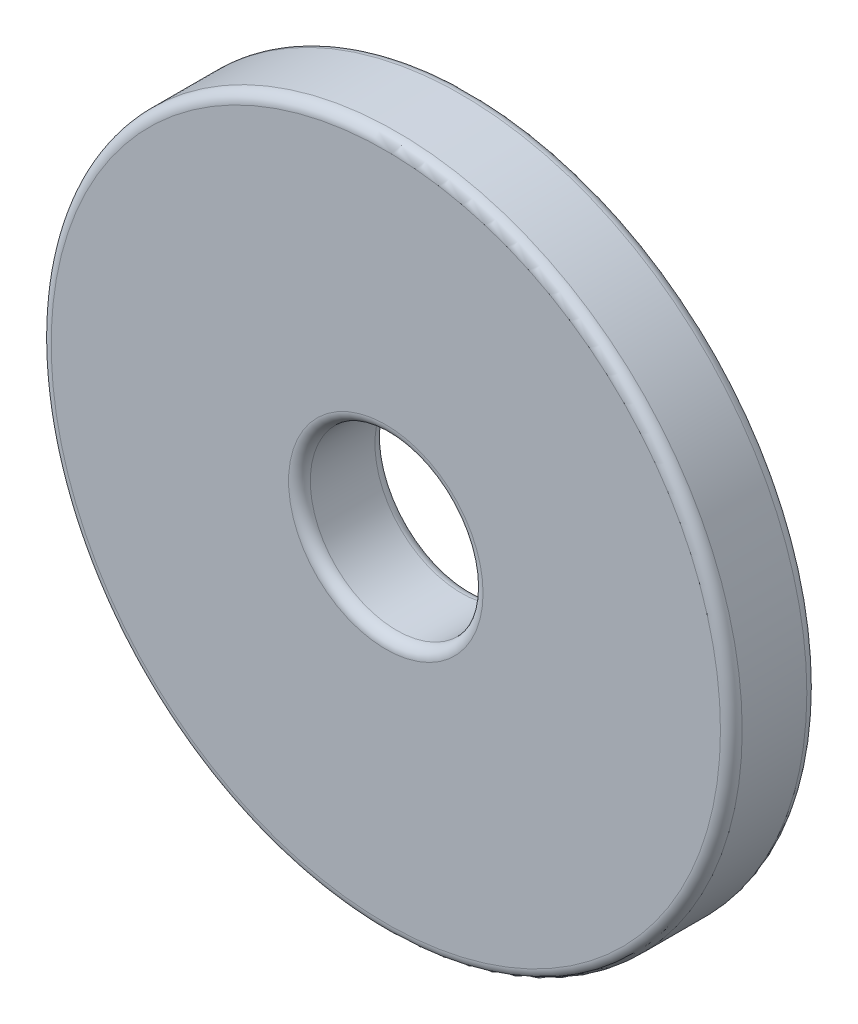
SolidWorks part; units mm, degrees
ref_plane "Front Plane" through (0, 0, 0) normal (0, 0, 1) x (1, 0, 0)
ref_plane "Top Plane" through (0, 0, 0) normal (0, 1, 0) x (1, 0, 0)
ref_plane "Right Plane" through (0, 0, 0) normal (1, 0, 0) x (0, 0, -1)
sketch "Sketch1" plane through (0, 0, 0) normal (0, 0, 1) x (1, 0, 0)
  circle A0 centre (68.3982, 3.2144) radius 6.35
  dimension "D1" = 12.7
extrude "Boss-Extrude1" add sketch "Sketch1" along normal blind 1.5875
sketch "Sketch2" plane through (0, 0, 0) normal (0, 0, -1) x (-1, 0, 0)
  circle A0 centre (-68.3982, 3.2144) radius 1.5875
  dimension "D1" = 3.175
extrude "Cut-Extrude1" cut sketch "Sketch2" against normal through all
fillet "Fillet1" radius 0.2 4 edges at (74.7482, 3.2144, 0) (66.8107, 3.2144, 0) (74.7482, 3.2144, 1.5875) (66.8107, 3.2144, 1.5875)
